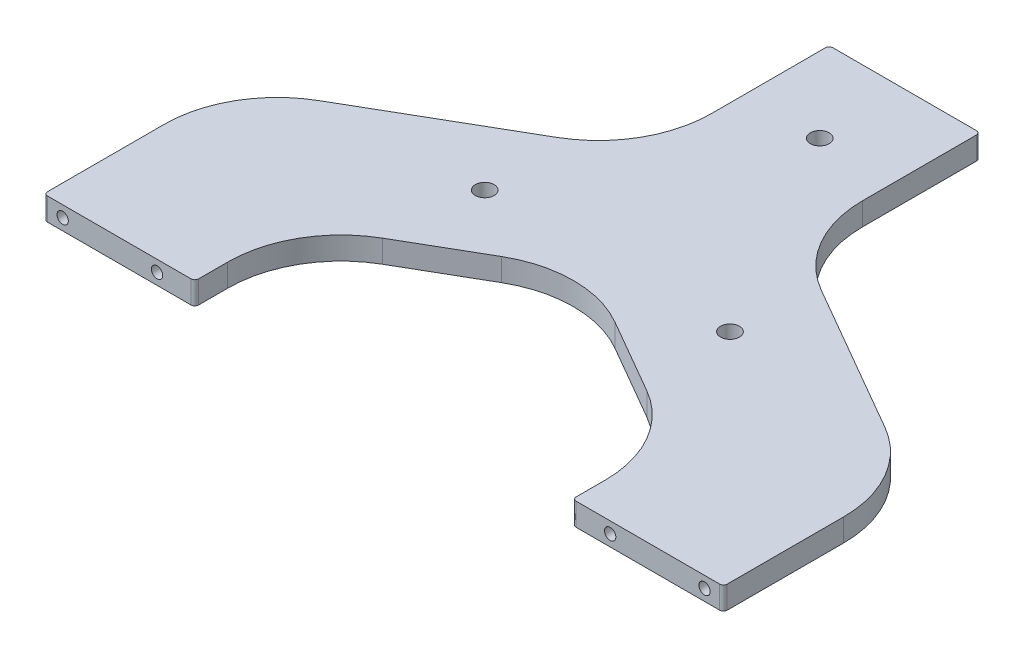
SolidWorks part; units mm, degrees
material "6061 合金"
ref_plane "前视基准面" through (0, 0, 0) normal (0, 0, 1) x (1, 0, 0)
ref_plane "上视基准面" through (0, 0, 0) normal (0, 1, 0) x (1, 0, 0)
ref_plane "右视基准面" through (0, 0, 0) normal (1, 0, 0) x (0, 0, -1)
other "Configuration Table"
sketch "草图1" plane through (0, 0, 0) normal (0, 1, 0) x (1, 0, 0)
  line L0 (0, 66.645) -> (0, 0) construction
  line L1 (0, 0) -> (-61.257, -35.3667) construction
  line L2 (0, 0) -> (64.9836, -37.5183) construction
  line L3 (-20, 60) -> (20, 60)
  line L4 (20, 60) -> (20, 11.547)
  line L5 (20, 11.547) -> (70, -17.3205)
  line L7 (0, 0) -> (89.4221, 51.6279) construction
  line L8 (0, 0) -> (0, -63.446) construction
  line L9 (0, 0) -> (-78.7072, 45.4416) construction
  line L10 (0, -23.094) -> (50, -51.9615)
  line L11 (-20, 60) -> (-20, 11.547)
  line L12 (-20, 11.547) -> (-70, -17.3205)
  line L14 (0, -23.094) -> (-50, -51.9615)
  line L15 (-116.2493, -78) -> (125.7289, -78) construction
  line L16 (70, -17.3205) -> (90, -28.8675)
  line L17 (90, -28.8675) -> (90, -78)
  line L18 (50, -51.9615) -> (50, -78)
  line L19 (50, -78) -> (90, -78)
  line L20 (-50, -78) -> (-90, -78)
  line L21 (-50, -51.9615) -> (-50, -78)
  line L22 (-90, -28.8675) -> (-90, -78)
  line L23 (-70, -17.3205) -> (-90, -28.8675)
  point P15 (77.9423, -45)
  point P17 (0, 60)
  dimension "D1" = 138
  dimension "D2" = 120
  dimension "D3" = 60
  dimension "D4" = 60
  dimension "D5" = 60
  dimension "D6" = 100
  dimension "D7" = 20
  dimension "D8" = 40
extrude "凸台-拉伸1" add sketch "草图1" along normal blind 6
sketch "草图3" plane through (0, 6, 0) normal (0, 1, 0) x (1, 0, 0)
  line L0 (0, 0) -> (0, 55.4456) construction
  line L1 (0, 0) -> (-62.5545, -36.1159) construction
  line L2 (0, 0) -> (50.5729, -29.1983) construction
  line L3 (90, -28.8675) -> (20, 11.547) construction
  line L4 (0, -23.094) -> (50, -51.9615) construction
  line L5 (-20, 11.547) -> (-90, -28.8675) construction
  line L6 (-50, -51.9615) -> (0, -23.094) construction
  line L7 (-32.475, -18.7494) -> (32.475, -18.7494) construction
  circle A0 centre (0, 37.4989) radius 2.5
  circle A1 centre (32.475, -18.7494) radius 2.5
  circle A2 centre (-32.475, -18.7494) radius 2.5
  circle A3 centre (0, 0) radius 37.4989 construction
  dimension "D1" = 5
  dimension "D2" = 64.95
extrude "切除-拉伸1" cut sketch "草图3" against normal blind 13 contours A0 | A1 | A2
sketch "草图4" plane through (0, 6, 0) normal (0, 1, 0) x (1, 0, 0)
  line L0 (0, 0) -> (0, 135.8563) construction
  line L1 (20, 60) -> (-20, 60) construction
  line L2 (-12.5, 60) -> (12.5, 60)
  line L3 (-12.5, 60) -> (-12.5, 65)
  line L4 (-12.5, 65) -> (12.5, 65)
  line L5 (12.5, 60) -> (12.5, 65)
  line L6 (70, -13.6383) -> (70, -101.0311) construction
  line L7 (50, -51.9615) -> (50, -78) construction
  line L8 (90, -78) -> (90, -28.8675) construction
  line L9 (50, -78) -> (90, -78) construction
  line L10 (57.5, -78) -> (82.5, -78)
  line L11 (57.5, -78) -> (57.5, -83)
  line L12 (57.5, -83) -> (82.5, -83)
  line L13 (82.5, -78) -> (82.5, -83)
  line L14 (-57.5, -83) -> (-82.5, -83)
  line L15 (-82.5, -78) -> (-82.5, -83)
  line L16 (-57.5, -78) -> (-82.5, -78)
  line L17 (-57.5, -78) -> (-57.5, -83)
  line M22 (-90, -78) -> (-50, -78)
  line M25 (50, -78) -> (90, -78)
  dimension "D3" = 5
  dimension "D1" = 5
  dimension "D2" = 25
  dimension "D4" = 25
extrude "凸台-拉伸2" [suppressed] add sketch "草图4" against normal blind 5 contours L17 L15 L14 M22 | L13 L11 L12 M25 | L4 L5 L2 L3
sketch "草图5" [suppressed] plane through (0, 5, 0) normal (0, 1, 0) x (1, 0, 0)
  line L0 (20, 100) -> (12.5, 100) construction
  line L1 (-12.5, 100) -> (-12.5, 105) construction
  line L2 (12.5, 100) -> (12.5, 105) construction
  line L3 (-12.5, 100) -> (-20, 100) construction
  line L4 (-75, -90) -> (-67.5, -90) construction
  line L5 (-107.5, -90) -> (-100, -90) construction
  line L6 (100, -90) -> (107.5, -90) construction
  line L7 (67.5, -90) -> (75, -90) construction
  line L8 (-75, -90) -> (-75, -95) construction
  line L9 (-100, -90) -> (-100, -95) construction
  line L10 (75, -90) -> (75, -95) construction
  line L11 (100, -90) -> (100, -95) construction
  circle A0 centre (14.05, 100) radius 1.55
  circle A1 centre (-14.05, 100) radius 1.55
  circle A2 centre (-73.45, -90) radius 1.55
  circle A3 centre (-101.55, -90) radius 1.55
  circle A4 centre (101.55, -90) radius 1.55
  circle A5 centre (73.45, -90) radius 1.55
  dimension "D2" = 3.1
extrude "切除-拉伸2" [suppressed] cut sketch "草图5" against normal blind 5
fillet "圆角1" radius 30 7 edges at (-90, 3, 28.8675) (-50, 3, 51.9615) (50, 3, 51.9615) (90, 3, 28.8675) (20, 3, -11.547) (0, 3, 23.094) (-20, 3, -11.547)
fillet "圆角2" radius 1 6 edges at (-50, 3, 78) (-90, 3, 78) (50, 3, 78) (90, 3, 78) (-20, 3, -60) (20, 3, -60)
sketch "草图6" plane through (0, 0, 78) normal (0, 0, 1) x (1, 0, 0)
  line L0 (-96.0706, 3) -> (112.618, 3) construction
  line L1 (51, 6) -> (89, 6) construction
  line L2 (51, 0) -> (89, 0) construction
  line L3 (0, 0) -> (0, 32.4606) construction
  line L4 (-15, 0) -> (15, 0) construction
  circle A0 centre (60, 3) radius 1.5
  circle A1 centre (85, 3) radius 1.5
  circle A2 centre (-85, 3) radius 1.5
  circle A3 centre (-60, 3) radius 1.5
  dimension "D1" = 3
  dimension "D2" = 60
  dimension "D3" = 25
extrude "切除-拉伸3" cut sketch "草图6" against normal blind 15
sketch "草图7" plane through (0, 0, -60) normal (0, 0, -1) x (-1, 0, 0)
  line L0 (-109.5799, 3) -> (108.7297, 3) construction
  line L1 (-19, 0) -> (19, 0) construction
  line L2 (-19, 6) -> (19, 6) construction
  line L3 (0, 0) -> (0, 19.4141) construction
  circle A0 centre (12.5, 3) radius 1.5
  circle A1 centre (-12.5, 3) radius 1.5
  dimension "D1" = 3
  dimension "D2" = 25
extrude "切除-拉伸4" cut sketch "草图7" against normal blind 15
